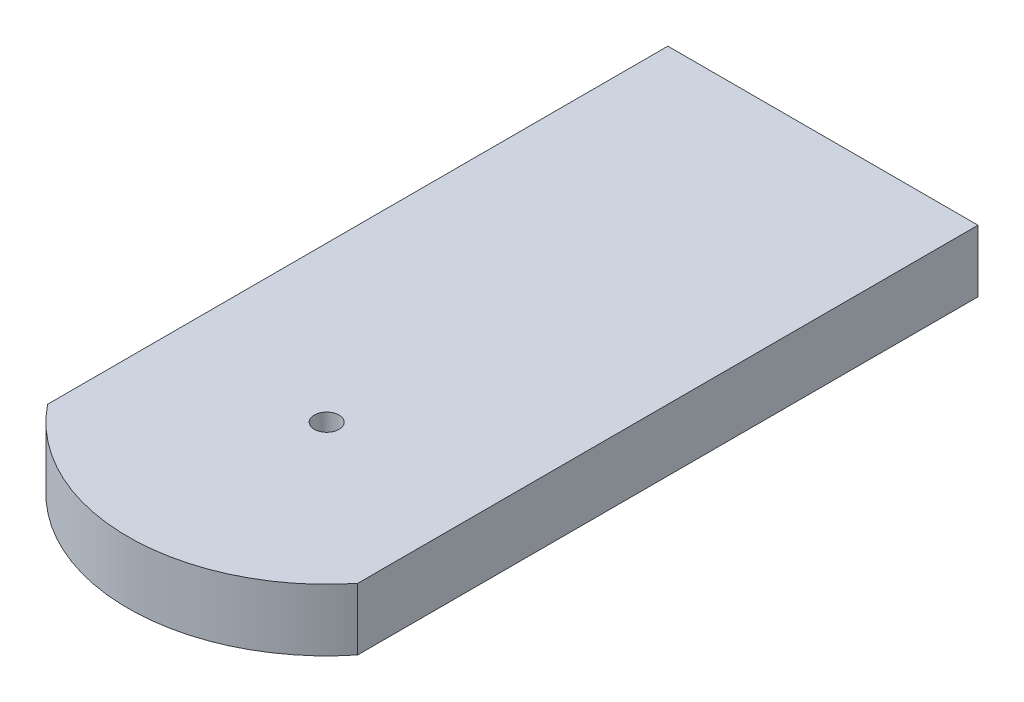
SolidWorks part; units mm, degrees
ref_plane "Front Plane" through (0, 0, 0) normal (0, 0, 1) x (1, 0, 0)
ref_plane "Top Plane" through (0, 0, 0) normal (0, 1, 0) x (1, 0, 0)
ref_plane "Right Plane" through (0, 0, 0) normal (1, 0, 0) x (0, 0, -1)
sketch "Sketch1" plane through (0, 0, 0) normal (0, 1, 0) x (1, 0, 0)
  line L0 (-1001.5418, -30) -> (48998.4582, -30) construction
  line L1 (-25, 50) -> (25, 50)
  line L2 (-25, 50) -> (-25, -50)
  line L3 (-25, -50) -> (25, -50)
  line L4 (25, 50) -> (25, -50)
  line L5 (-25, 50) -> (25, -50) construction
  line L6 (-25, -50) -> (25, 50) construction
  line L7 (0, -1000) -> (0, 49000) construction
  circle A0 centre (0, -30) radius 2
  arc A1 (-25, -50) -> (25, -50) centre (0, -30) ccw
  point P0 (0, 0)
  dimension "D3" = 4
  dimension "D1" = 100
  dimension "D2" = 20
  dimension "D4" = 50
extrude "Boss-Extrude1" add sketch "Sketch1" along normal blind 10 contours L4 L1 L2 L3 A0 | L3 A1
